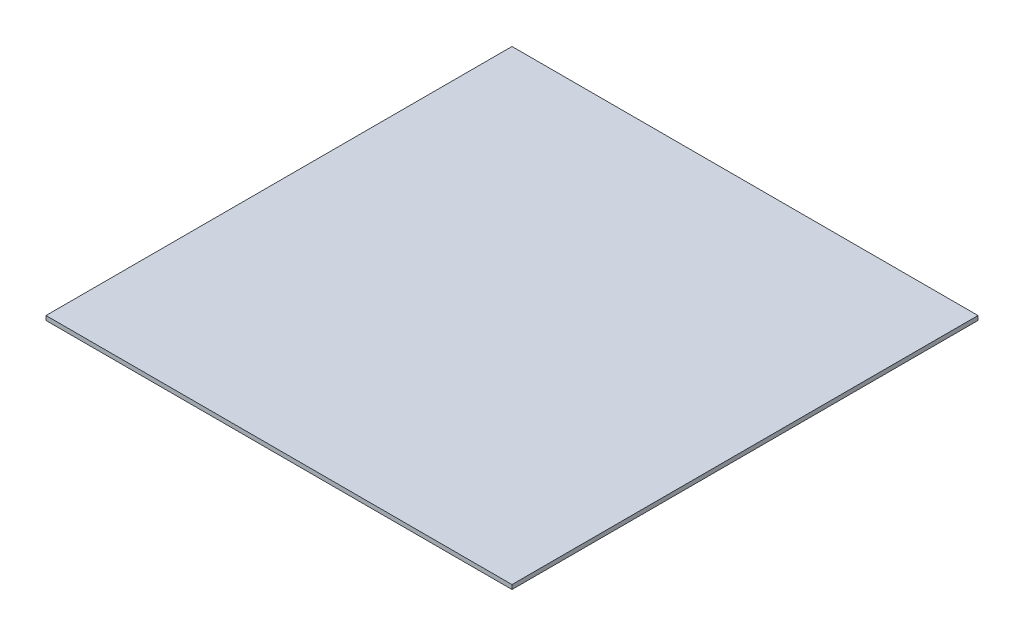
SolidWorks part; units mm, degrees
material "6061-T6 (SS)"
ref_plane "Front Plane" through (0, 0, 0) normal (0, 0, 1) x (1, 0, 0)
ref_plane "Top Plane" through (0, 0, 0) normal (0, 1, 0) x (1, 0, 0)
ref_plane "Right Plane" through (0, 0, 0) normal (1, 0, 0) x (0, 0, -1)
sketch "Sketch1" plane through (0, 0, 0) normal (0, 1, 0) x (1, 0, 0)
  line L1 (0, 0) -> (-685.8, 0)
  line L2 (0, 0) -> (0, 685.8)
  line L3 (0, 685.8) -> (-685.8, 685.8)
  line L4 (-685.8, 0) -> (-685.8, 685.8)
  dimension "D1" = 685.8
  dimension "D2" = 685.8
extrude "Boss-Extrude1" add sketch "Sketch1" along normal blind 6.35
equation "\"D2@Sketch1\"=\"D1@Sketch1\""
